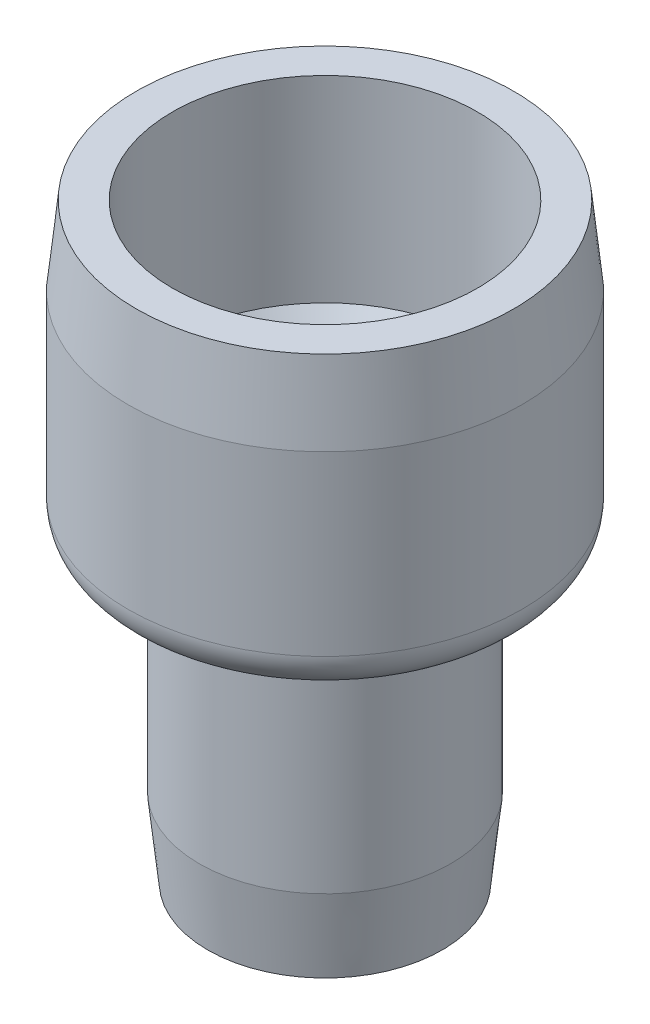
SolidWorks part; units mm, degrees
ref_plane "Front Plane" through (0, 0, 0) normal (0, 0, 1) x (1, 0, 0)
ref_plane "Top Plane" through (0, 0, 0) normal (0, 1, 0) x (1, 0, 0)
ref_plane "Right Plane" through (0, 0, 0) normal (1, 0, 0) x (0, 0, -1)
sketch "Sketch1" plane through (0, 0, 0) normal (0, 1, 0) x (1, 0, 0)
  circle A0 centre (0, 0) radius 6.375
  dimension "D1" = 12.75
extrude "Boss-Extrude1" add sketch "Sketch1" along normal blind 15
sketch "Sketch9" plane through (0, 15, 0) normal (0, 1, 0) x (1, 0, 0)
  circle A0 centre (0, 0) radius 10
  dimension "D1" = 20
extrude "Boss-Extrude5" add sketch "Sketch9" along normal blind 15
sketch "Sketch10" plane through (0, 30, 0) normal (0, 1, 0) x (1, 0, 0)
  circle A0 centre (0, 0) radius 7.75
  circle A1 centre (0, 0) radius 10 construction
  dimension "D1" = 2.25
extrude "Cut-Extrude4" cut sketch "Sketch10" against normal blind 10
sketch "Sketch11" plane through (0, 20, 0) normal (0, 1, 0) x (1, 0, 0)
  circle A0 centre (0, 0) radius 7.75
extrude "Cut-Extrude5" cut sketch "Sketch11" against normal blind 7 draft 35
sketch "Sketch12" plane through (0, 0, 0) normal (0, -1, 0) x (1, 0, 0)
  circle A0 centre (0, 0) radius 4.125
  circle A1 centre (0, 0) radius 6.375 construction
  dimension "D1" = 2.25
extrude "Cut-Extrude6" cut sketch "Sketch12" against normal blind 20
chamfer "Chamfer1" distance 4 angle 6 1 edges at (0, 30, 10)
chamfer "Chamfer2" distance 4 angle 6 1 edges at (0, 0, 6.375)
fillet "Fillet2" radius 2 1 edges at (0, 15, 10)
